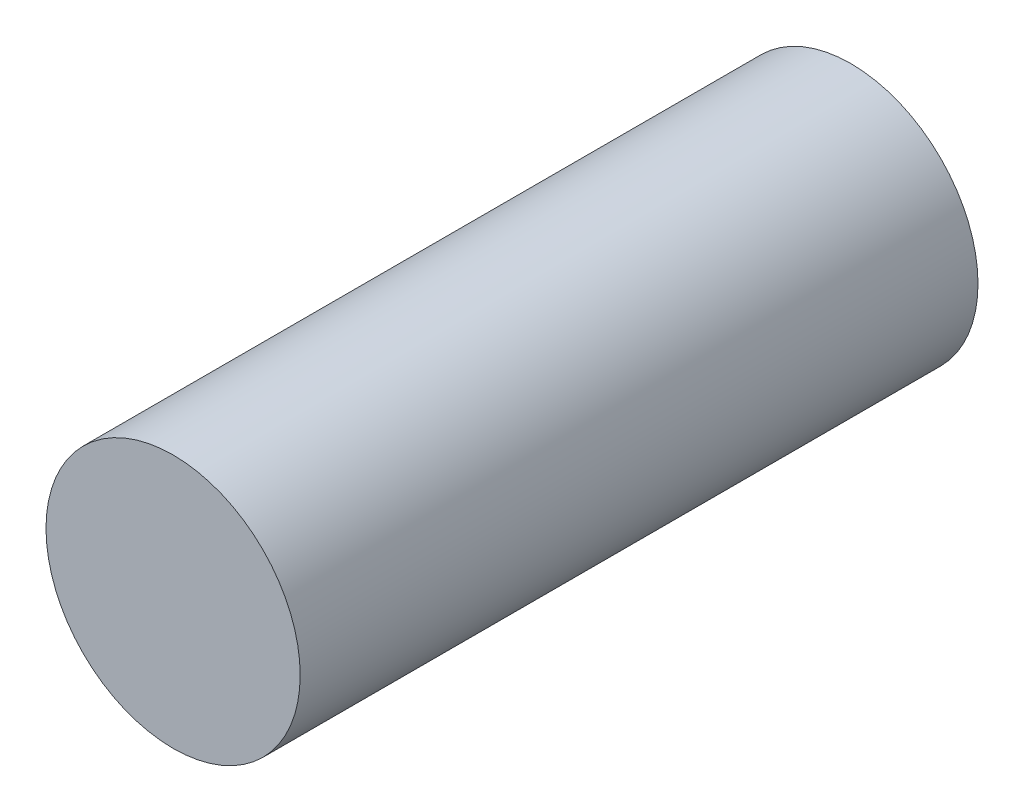
SolidWorks part; units mm, degrees
material "1060 Alloy"
ref_plane "Front Plane" through (0, 0, 0) normal (0, 0, 1) x (1, 0, 0)
ref_plane "Top Plane" through (0, 0, 0) normal (0, 1, 0) x (1, 0, 0)
ref_plane "Right Plane" through (0, 0, 0) normal (1, 0, 0) x (0, 0, -1)
sketch "Sketch1" plane through (0, 0, 0) normal (0, 0, 1) x (1, 0, 0)
  circle A0 centre (0, 0) radius 3
  dimension "D1" = 6
extrude "Boss-Extrude1" add sketch "Sketch1" along normal blind 16
